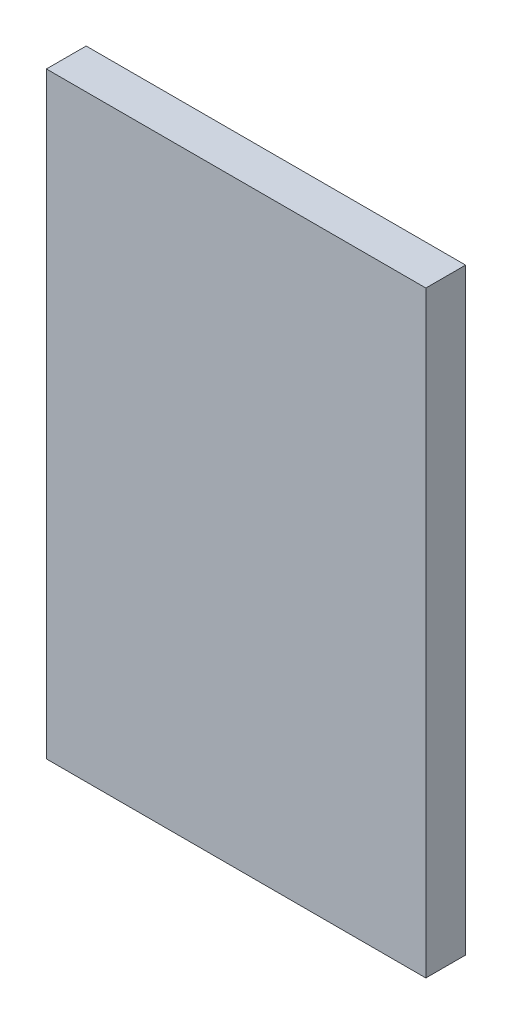
SolidWorks part; units mm, degrees
ref_plane "Front Plane" through (0, 0, 0) normal (0, 0, 1) x (1, 0, 0)
ref_plane "Top Plane" through (0, 0, 0) normal (0, 1, 0) x (1, 0, 0)
ref_plane "Right Plane" through (0, 0, 0) normal (1, 0, 0) x (0, 0, -1)
sketch "Sketch1" plane through (0, 0, 0) normal (0, 0, 1) x (1, 0, 0)
  line L1 (0, 0) -> (25.4, 0)
  line L2 (0, 0) -> (0, 40)
  line L3 (0, 40) -> (25.4, 40)
  line L4 (25.4, 0) -> (25.4, 40)
  dimension "D1" = 25.4
  dimension "D2" = 40
extrude "Boss-Extrude1" add sketch "Sketch1" along normal blind 2.66
